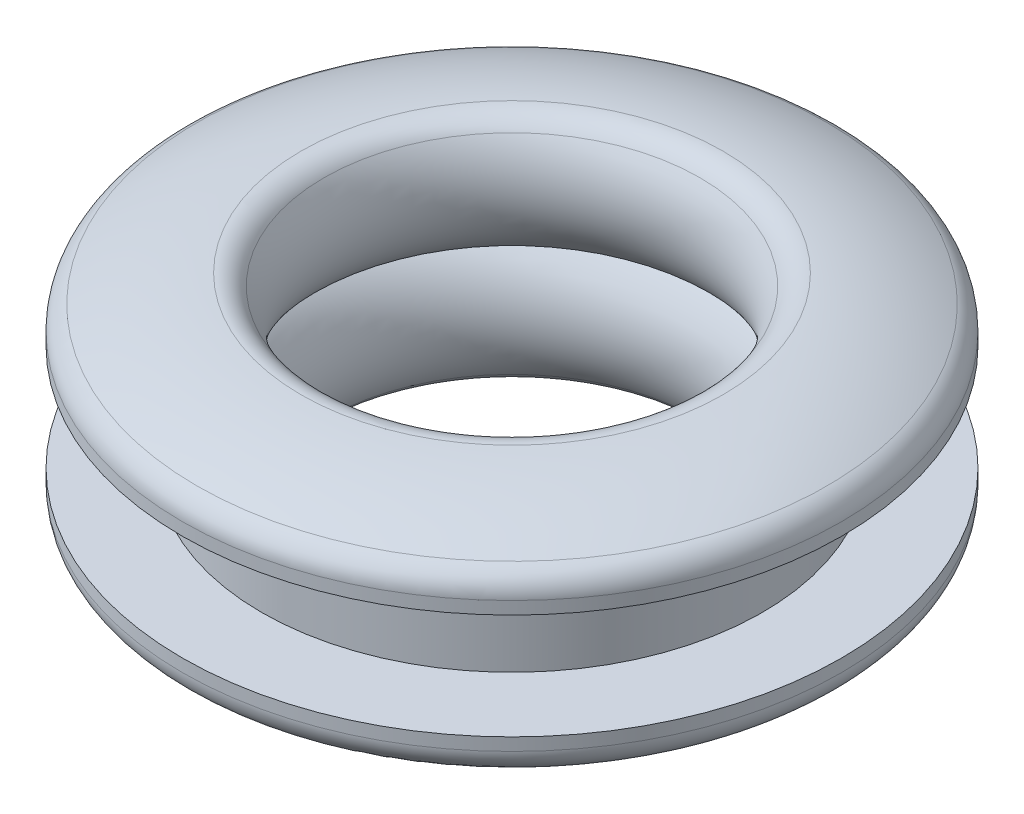
SolidWorks part; units mm, degrees
ref_plane "前视基准面" through (0, 0, 0) normal (0, 0, 1) x (1, 0, 0)
ref_plane "上视基准面" through (0, 0, 0) normal (0, 1, 0) x (1, 0, 0)
ref_plane "右视基准面" through (0, 0, 0) normal (1, 0, 0) x (0, 0, -1)
sketch "草图1" plane through (0, 0, 0) normal (0, 0, 1) x (1, 0, 0)
  line L0 (0, 0) -> (0, -44.1667) construction
  line L1 (0, -44.1667) -> (50, -44.1667) construction
  line L2 (50, -24.7892) -> (50, -20)
  line L3 (50, -20) -> (20, -20)
  line L4 (20, -20) -> (20, 0)
  line L5 (20, 0) -> (0, 0)
  line L6 (-75, 0) -> (-75, -44.1667) construction
  arc A0 (0, -44.1667) -> (44.4444, -33.7473) centre (0, 55.8333) ccw
  arc A1 (50, -24.7892) -> (44.4444, -33.7473) centre (40, -24.7892) cw
  arc A2 (0, 0) -> (0, -44.1667) centre (22.0833, -22.0833) ccw
  dimension "D1" = 10
  dimension "D3" = 100
  dimension "D2" = 20
  dimension "D4" = 20
  dimension "D5" = 75
  dimension "D6" = 40
  dimension "D7" = 55.8333
revolve "旋转2" add sketch "草图1" angle 360 about L6
mirror "镜向1" about plane through (0, 0, 0) normal (0, 1, 0) of bodies 107
fillet "圆角1" radius 10 2 edges at (-75, -44.1667, 75) (-75, 44.1667, 75)
